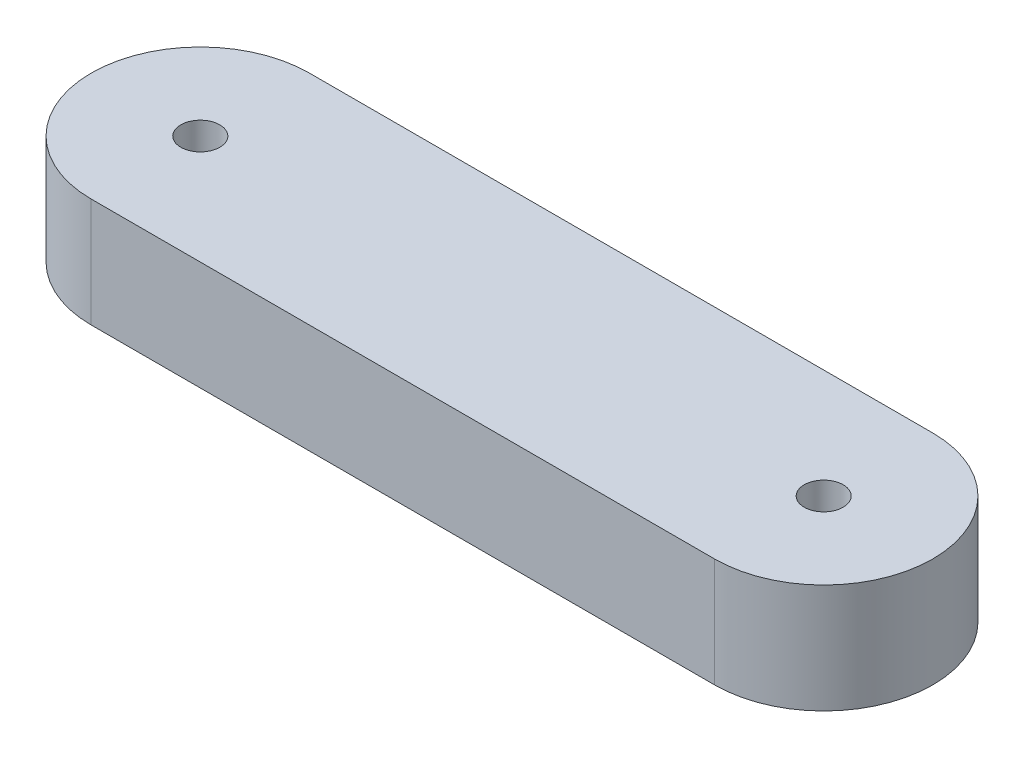
SolidWorks part; units mm, degrees
ref_plane "Front Plane" through (0, 0, 0) normal (0, 0, 1) x (1, 0, 0)
ref_plane "Top Plane" through (0, 0, 0) normal (0, 1, 0) x (1, 0, 0)
ref_plane "Right Plane" through (0, 0, 0) normal (1, 0, 0) x (0, 0, -1)
sketch "Sketch1" plane through (0, 0, 0) normal (0, 1, 0) x (1, 0, 0)
  line L1 (0, 21) -> (120, 21)
  line L2 (0, -21) -> (120, -21)
  circle A0 centre (0, 0) radius 3.75
  circle A1 centre (120, 0) radius 3.75
  arc A2 (0, 21) -> (0, -21) centre (0, 0) ccw
  arc A3 (120, -21) -> (120, 21) centre (120, 0) ccw
extrude "Boss-Extrude1" add sketch "Sketch1" along normal blind 21
sketch "Sketch2" plane through (0, 0, 0) normal (0, -1, 0) x (1, 0, 0)
  point P0 (0, 0)
